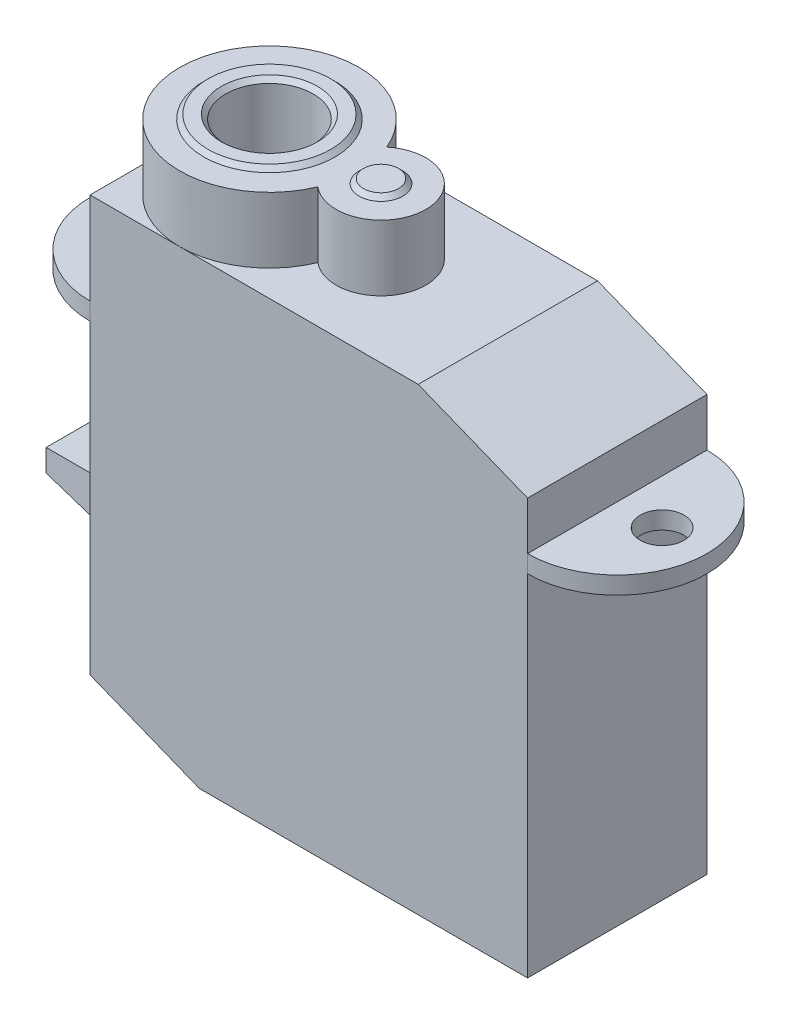
SolidWorks part; units mm, degrees
material "Custom Plastic"
ref_plane "Front Plane" through (0, 0, 0) normal (0, 0, 1) x (1, 0, 0)
ref_plane "Top Plane" through (0, 0, 0) normal (0, 1, 0) x (1, 0, 0)
ref_plane "Right Plane" through (0, 0, 0) normal (1, 0, 0) x (0, 0, -1)
sketch "Sketch1" plane through (0, 0, 0) normal (0, 1, 0) x (1, 0, 0)
  line L1 (0, 0) -> (20, 0)
  line L2 (0, 0) -> (0, -8.2)
  line L3 (0, -8.2) -> (20, -8.2)
  line L4 (20, 0) -> (20, -8.2)
  dimension "D1" = 20
  dimension "D2" = 8.2
extrude "Boss-Extrude1" add sketch "Sketch1" along normal blind 21
sketch "Sketch2" plane through (20, 0, 0) normal (1, 0, 0) x (0, 0, -1)
  line L0 (-8.2, 21) -> (-8.2, 0) construction
  line L1 (-8.2, 16.8) -> (0, 16.8)
  line L2 (-8.2, 16.8) -> (-8.2, 16)
  line L3 (-8.2, 16) -> (0, 16)
  line L4 (0, 16.8) -> (0, 16)
  line L5 (0, 21) -> (0, 0) construction
  line L6 (-8.2, 0) -> (0, 0) construction
  dimension "D1" = 16
  dimension "D2" = 0.8
extrude "Boss-Extrude2" add sketch "Sketch2" along normal blind 5 contours L3 L4 L1 L2
sketch "Sketch3" plane through (0, 0, 0) normal (-1, 0, 0) x (0, 0, 1)
  line L0 (0, 21) -> (0, 0) construction
  line L1 (0, 16) -> (8.2, 16)
  line L2 (0, 16) -> (0, 16.8)
  line L3 (0, 16.8) -> (8.2, 16.8)
  line L4 (8.2, 16) -> (8.2, 16.8)
  line L5 (8.2, 21) -> (8.2, 0) construction
  line L6 (0, 0) -> (8.2, 0) construction
  dimension "D1" = 16
  dimension "D2" = 0.8
extrude "Boss-Extrude3" add sketch "Sketch3" along normal blind 5
sketch "Sketch4" plane through (0, 0, 8.2) normal (0, 0, 1) x (1, 0, 0)
  line L0 (20, 19) -> (15, 21)
  line L1 (20, 21) -> (20, 16.8) construction
  line L2 (0, 21) -> (20, 21) construction
  line L3 (15, 21) -> (20, 21)
  line L4 (20, 21) -> (20, 19)
  dimension "D1" = 5
  dimension "D2" = 2
extrude "Cut-Extrude1" cut sketch "Sketch4" against normal up to next
ref_plane "Plane1" through (0, 16.8, 0) normal (0, 1, 0) x (1, 0, 0)
sketch "Sketch8" plane through (0, 16.8, 0) normal (0, 1, 0) x (1, 0, 0)
  line L0 (0, -8.2) -> (0, 0) construction
  line L1 (20, -8.2) -> (20, 0) construction
  line L4 (-5, 0) -> (0, 0)
  line L6 (-5, -8.2) -> (0, -8.2) construction
  line L7 (-5, -8.2) -> (0, -8.2)
  line L9 (20, -8.2) -> (25, -8.2)
  line L10 (25, -8.2) -> (20, -8.2) construction
  line L13 (25, 0) -> (20, 0) construction
  line L14 (25, 0) -> (20, 0)
  line L15 (25, 0) -> (25, -8.2)
  line L16 (-5, 0) -> (-5, -8.2)
  arc A0 (0, 0) -> (0, -8.2) centre (0, -4.1) ccw
  arc A1 (20, -8.2) -> (20, 0) centre (20, -4.1) ccw
extrude "Cut-Extrude2" cut sketch "Sketch8" against normal up to next
sketch "Sketch9" plane through (0, 16.8, 0) normal (0, 1, 0) x (1, 0, 0)
  line L0 (-4.1, -4.1) -> (0, -4.1) construction
  line L1 (20, -4.1) -> (24.1, -4.1) construction
  line L2 (20, -8.2) -> (20, 0) construction
  arc A0 (0, 0) -> (0, -8.2) centre (0, -4.1) ccw construction
  arc A1 (20, -8.2) -> (20, 0) centre (20, -4.1) ccw construction
  circle A4 centre (-2.05, -4.1) radius 1
  circle A5 centre (22.05, -4.1) radius 1
  dimension "D1" = 2
  dimension "D2" = 2
hole_wizard "Ø2.0 (2) Diameter Hole1" positions "3DSketch1" profile "Sketch14" hole size "Ø2.0" standard "ANSI Metric" end condition up to next
sketch3d "3DSketch1"
  point P0 (-2.05, 16.8, 4.1)
  point P3 (22.05, 16.8, 4.1)
sketch "Sketch14" plane through (-2.05, 16.8, 4.1) normal (1, 0, 0) x (0, 0, 1)
  line L0 (0, 0) -> (0, 0.8)
  line L1 (0, 0.8) -> (1, 0.8)
  line L2 (1, 0.8) -> (1, 0)
  line L5 (1, 0) -> (0, 0)
  line L11 (0, -6.35) -> (0, 107.95) construction
  dimension "Thru Hole Dia." = 2
  dimension "Thru Hole Depth" = 0.8
sketch "Sketch10" plane through (0, 21, 0) normal (0, 1, 0) x (1, 0, 0)
  line L0 (15, 0) -> (0, 0) construction
  line L1 (0, -8.2) -> (15, -8.2) construction
  line L2 (0, 0) -> (0, -8.2) construction
  line L3 (9.2, 0) -> (9.2, -4.1) construction
  line L4 (9.2, -4.1) -> (8.2, -4.1) construction
  arc A0 (7.886, -2.5265) -> (7.886, -5.6735) centre (4.1, -4.1) ccw
  arc A1 (7.886, -5.6735) -> (7.886, -2.5265) centre (9.2, -4.1) ccw
  arc A2 (7.886, -2.5265) -> (7.886, -5.6735) centre (4.1, -4.1) cw construction
  point P11 (9.2, -2.05)
  dimension "D1" = 1
extrude "Boss-Extrude6" add sketch "Sketch10" along normal blind 3
sketch "Sketch11" plane through (0, 0, 8.2) normal (0, 0, 1) x (1, 0, 0)
  line L0 (0, 0) -> (0, 2)
  line L1 (0, 16) -> (0, 0) construction
  line L2 (0, 2) -> (5, 0)
  line L3 (0, 0) -> (20, 0) construction
  line L4 (5, 0) -> (0, 0)
  dimension "D1" = 2
  dimension "D2" = 5
extrude "Cut-Extrude4" cut sketch "Sketch11" against normal up to next
sketch "Sketch12" plane through (0, 0, 0) normal (-1, 0, 0) x (0, 0, 1)
  line L0 (4.1, 16) -> (4.1, 0) construction
  line L1 (0, 16) -> (8.2, 16) construction
  line L2 (0, 0) -> (8.2, 0) construction
  line L4 (1, 7) -> (7.2, 7)
  line L5 (1, 7) -> (1, 9)
  line L6 (1, 9) -> (7.2, 9)
  line L7 (7.2, 7) -> (7.2, 9)
  line L8 (1, 7) -> (7.2, 9) construction
  line L9 (1, 9) -> (7.2, 7) construction
  line L10 (0, 16) -> (0, 2) construction
  point P8 (4.1, 8)
  point P13 (7.3548, 8.9154)
  dimension "D1" = 2
  dimension "D2" = 1
extrude "Boss-Extrude7" add sketch "Sketch12" along normal blind 3.5 draft 8
sketch "Sketch15" plane through (0, 24, 0) normal (0, 1, 0) x (1, 0, 0)
  circle A0 centre (4.1, -4.1) radius 2
  dimension "D1" = 4
extrude "Cut-Extrude5" cut sketch "Sketch15" against normal blind 5
sketch "Sketch17" plane through (0, 24, 0) normal (0, 1, 0) x (1, 0, 0)
  circle A0 centre (4.1, -4.1) radius 2
  circle A1 centre (4.1, -4.1) radius 3
  circle A2 centre (9.2, -4.1) radius 1
  dimension "D1" = 4
  dimension "D2" = 1
  dimension "D3" = 2
extrude "Boss-Extrude10" add sketch "Sketch17" along normal blind 0.2 draft 45
